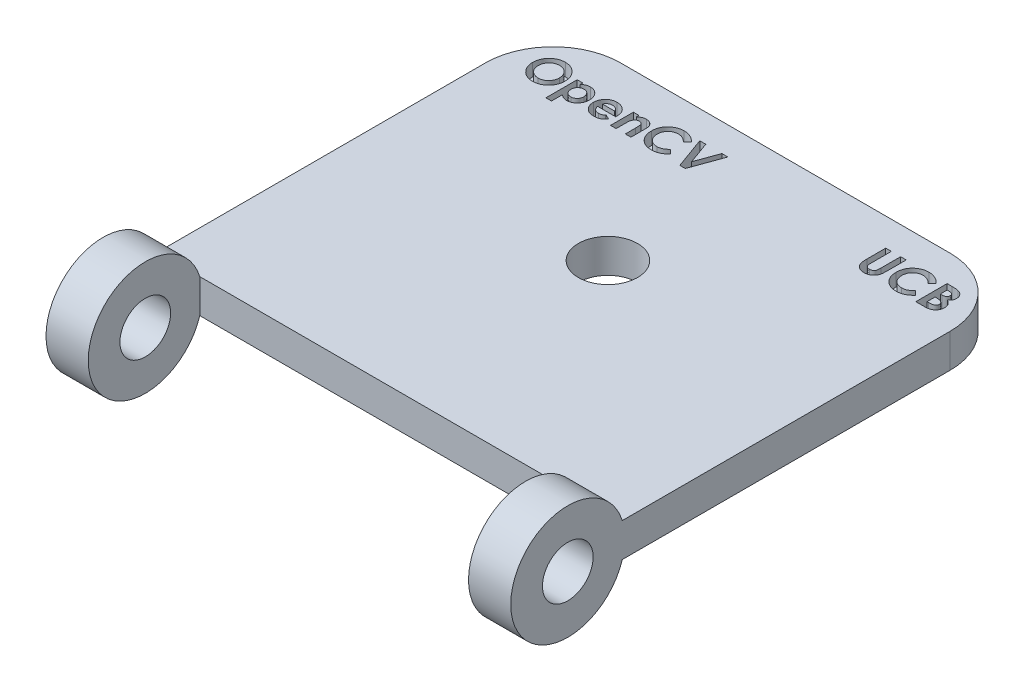
SolidWorks part; units mm, degrees
ref_plane "Alzado" through (0, 0, 0) normal (0, 0, 1) x (1, 0, 0)
ref_plane "Planta" through (0, 0, 0) normal (0, 1, 0) x (1, 0, 0)
ref_plane "Vista lateral" through (0, 0, 0) normal (1, 0, 0) x (0, 0, -1)
sketch "Croquis1" plane through (0, 0, 0) normal (0, 1, 0) x (1, 0, 0)
  line L1 (-27.5, -30) -> (27.5, -30)
  line L2 (-27.5, -30) -> (-27.5, 30)
  line L3 (-27.5, 30) -> (27.5, 30)
  line L4 (27.5, -30) -> (27.5, 30)
  line L5 (-27.5, -30) -> (27.5, 30) construction
  line L6 (-27.5, 30) -> (27.5, -30) construction
  point P0 (0, 0)
  dimension "D1" = 55
  dimension "D2" = 60
extrude "Saliente-Extruir1" add sketch "Croquis1" along normal blind 4
sketch "Croquis2" plane through (27.5, 0, 0) normal (1, 0, 0) x (0, 0, -1)
  line L0 (-30, 2) -> (-23.25, 2) construction
  line L1 (-30, 4) -> (-30, 0) construction
  circle A0 centre (-23.25, 2) radius 6.75
  circle A1 centre (-23.25, 2) radius 3
  dimension "D2" = 6
  dimension "D1" = 6.75
extrude "Saliente-Extruir2" add sketch "Croquis2" against normal up to surface (55 mm away) contours A0 up to face at (-27.5, 2, 0)
sketch "Croquis3" plane through (27.5, 0, 0) normal (1, 0, 0) x (0, 0, -1)
  line L0 (-23.25, 8.75) -> (-23.25, -4.75)
  arc A0 (-16.8031, 4) -> (-29.6969, 4) centre (-23.25, 2) ccw construction
  arc A1 (-29.6969, 0) -> (-16.8031, 0) centre (-23.25, 2) ccw construction
  circle A2 centre (-23.25, 2) radius 3
  dimension "D1" = 6
extrude "Cortar-Extruir1" cut sketch "Croquis3" against normal up to surface (55 mm away) contours L0 A2 | L0 A2 up to face at (-27.5, 2, 11.625)
sketch "Croquis4" plane through (27.5, 0, 0) normal (1, 0, 0) x (0, 0, -1)
  line L0 (-29.6969, 4) -> (-30.3405, 4)
  line L1 (-30.3405, 4) -> (-30.3405, 0)
  line L2 (-30.3405, 0) -> (-29.6969, 0)
  arc A2 (-29.6969, 0) -> (-29.6969, 4) centre (-23.25, 2) cw
  arc A3 (-29.6969, 0) -> (-16.8031, 0) centre (-23.25, 2) ccw construction
  arc A4 (-16.8031, 4) -> (-29.6969, 4) centre (-23.25, 2) ccw construction
extrude "Cortar-Extruir4" cut sketch "Croquis4" against normal blind 72
sketch "Croquis5" plane through (0, 0, 0) normal (0, -1, 0) x (1, 0, 0)
  line L0 (0, -30) -> (0, -9) construction
  line L1 (27.5, -30) -> (-27.5, -30) construction
  circle A0 centre (0, -9) radius 3.5
  dimension "D2" = 7
  dimension "D1" = 21
extrude "Cortar-Extruir5" cut sketch "Croquis5" against normal blind 72
sketch "Croquis6" plane through (0, 4, 0) normal (0, 1, 0) x (1, 0, 0)
  line L0 (0, 30) -> (0, 23) construction
  line L1 (27.5, 30) -> (-27.5, 30) construction
  line L2 (25, 23) -> (-25, 23) construction
  text T0 "OpenCV" font "Century Gothic" height in points 14
  text T1 "UCB" font "Century Gothic" height in points 14
  point P8 (0, 23)
  point P10 (0, 23)
  dimension "D1" = 7
  dimension "D2" = 50
extrude "Cortar-Extruir6" cut sketch "Croquis6" against normal blind 1.5
sketch "Croquis7" plane through (0, 4, 0) normal (0, 1, 0) x (1, 0, 0)
  line L0 (-22.5, -16.8031) -> (22.5, -16.8031) construction
  line L1 (-27.5, -16.8031) -> (27.5, -16.8031) construction
  line L2 (0, 0) -> (0, -16.8031) construction
  line L4 (-22.5, -16.8031) -> (22.5, -16.8031)
  line L5 (-22.5, -16.8031) -> (-22.5, -31.783)
  line L6 (-22.5, -31.783) -> (22.5, -31.783)
  line L7 (22.5, -16.8031) -> (22.5, -31.783)
  point P5 (0, -16.8031)
  dimension "D1" = 45
extrude "Cortar-Extruir8" cut sketch "Croquis7" against normal through all both and the other way through all
fillet "Redondeo1" radius 8 2 edges at (-27.5, 2, -30) (27.5, 2, -30)
